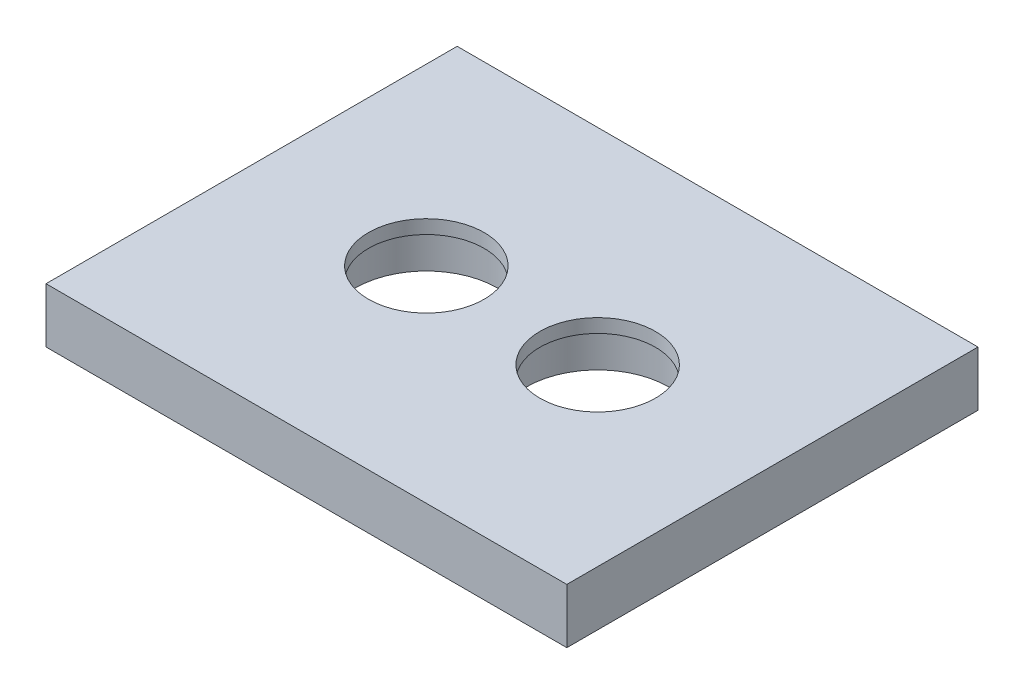
SolidWorks part; units mm, degrees
ref_plane "Ön Düzlem" through (0, 0, 0) normal (0, 0, 1) x (1, 0, 0)
ref_plane "Üst Düzlem" through (0, 0, 0) normal (0, 1, 0) x (1, 0, 0)
ref_plane "Sağ Düzlem" through (0, 0, 0) normal (1, 0, 0) x (0, 0, -1)
sketch "Sketch1" plane through (0, 0, 0) normal (0, 1, 0) x (1, 0, 0)
  line L1 (-95, -75) -> (95, -75)
  line L2 (-95, -75) -> (-95, 75)
  line L3 (-95, 75) -> (95, 75)
  line L4 (95, -75) -> (95, 75)
  line L5 (-95, -75) -> (95, 75) construction
  line L6 (-95, 75) -> (95, -75) construction
  point P0 (0, 0)
  dimension "D1" = 190
  dimension "D2" = 150
extrude "Boss-Extrude1" add sketch "Sketch1" along normal blind 20
sketch "Sketch2" plane through (0, 20, 0) normal (0, 1, 0) x (1, 0, 0)
  circle A0 centre (31.25, 0) radius 26
  circle A1 centre (-31.25, 0) radius 26
  dimension "D3" = 52
  dimension "D1" = 31.25
  dimension "D2" = 31.25
extrude "Cut-Extrude1" cut sketch "Sketch2" against normal up to next
sketch "Sketch7" plane through (0, 20, 0) normal (0, 1, 0) x (1, 0, 0)
  line L0 (-95, 75) -> (-95, -75) construction
  line L1 (95, 75) -> (-95, 75) construction
  line L2 (-95, -75) -> (95, -75) construction
  line L3 (95, -75) -> (95, 75) construction
  circle A0 centre (-70, 55) radius 3
  circle A1 centre (-70, -55) radius 3
  circle A2 centre (0, -55) radius 3
  circle A3 centre (0, 55) radius 3
  circle A4 centre (70, 55) radius 3
  circle A5 centre (70, -55) radius 3
  dimension "D1" = 6
  dimension "D2" = 25
  dimension "D3" = 20
  dimension "D4" = 20
  dimension "D5" = 25
sketch "Sketch9" plane through (0, 20, 0) normal (0, 1, 0) x (1, 0, 0)
  line L4 (95, -75) -> (95, 75)
  line L5 (95, 75) -> (-95, 75)
  line L6 (-95, 75) -> (-95, -75)
  line L7 (-95, -75) -> (95, -75)
  line L8 (95, -75) -> (95, 75)
  line L9 (95, 75) -> (-95, 75)
  line L10 (-95, 75) -> (-95, -75)
  line L11 (-95, -75) -> (95, -75)
  circle A0 centre (31.25, 0) radius 26 construction
  circle A1 centre (31.25, 0) radius 26
  circle A2 centre (-31.25, 0) radius 26 construction
  circle A3 centre (-31.25, 0) radius 26
  circle A4 centre (-31.25, 0) radius 21.1
  circle A5 centre (31.25, 0) radius 21.1
  circle M11 centre (-31.25, 0) radius 26
  circle M12 centre (31.25, 0) radius 26
  dimension "D2" = 42.2
  dimension "D1" = 0
extrude "Boss-Extrude2" add sketch "Sketch9" against normal blind 5 contours A4 M11 | A5 M12
